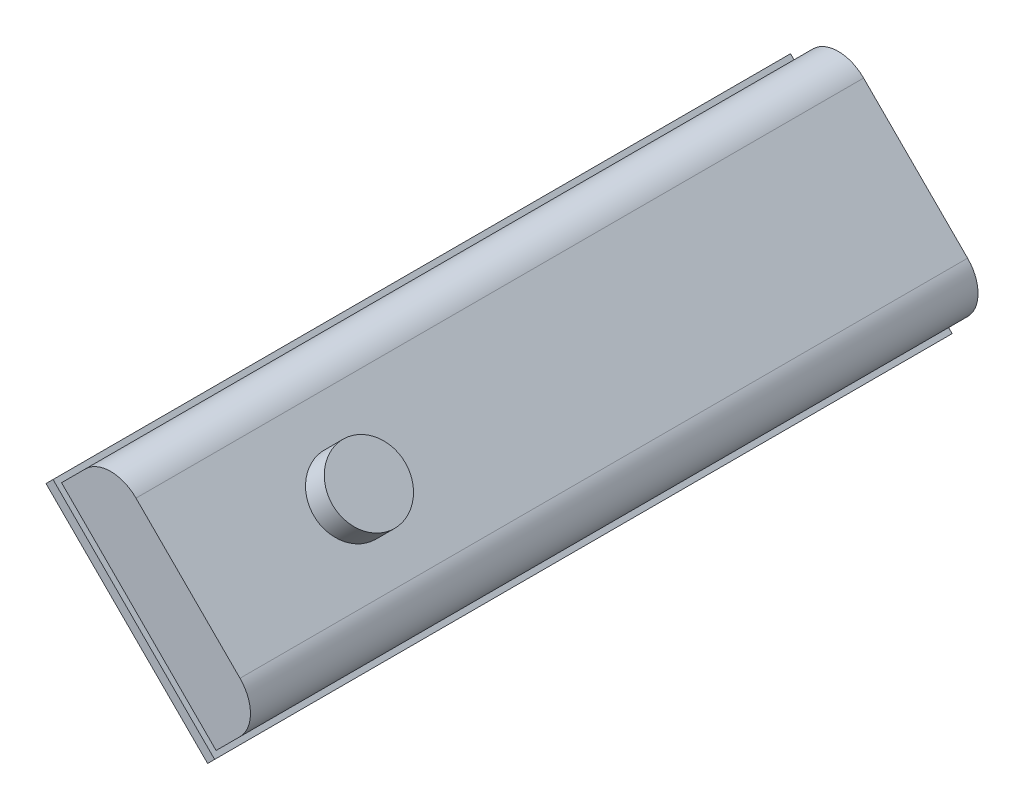
SolidWorks part; units mm, degrees
ref_plane "Front Plane" through (0, 0, 0) normal (0, 0, 1) x (1, 0, 0)
ref_plane "Top Plane" through (0, 0, 0) normal (0, 1, 0) x (1, 0, 0)
ref_plane "Right Plane" through (0, 0, 0) normal (1, 0, 0) x (0, 0, -1)
other "Configuration Table"
sketch "Sketch1" plane through (0, 0, 0) normal (0, 0, 1) x (1, 0, 0)
  line L0 (193.7119, 287.05) -> (287.05, 193.7119)
  line L1 (287.05, 193.7119) -> (305.7176, 212.3795)
  line L2 (305.7176, 242.9265) -> (242.9265, 305.7176)
  line L3 (212.3795, 305.7176) -> (193.7119, 287.05)
  arc A0 (305.7176, 212.3795) -> (305.7176, 242.9265) centre (290.4441, 227.653) ccw
  arc A1 (242.9265, 305.7176) -> (212.3795, 305.7176) centre (227.653, 290.4441) ccw
extrude "Cover" add sketch "Sketch1" along normal blind 439.28 from offset 375.38
sketch "Sketch2" plane through (0, 0, 0) normal (0, 0, 1) x (1, 0, 0)
  line L0 (191.5906, 289.1713) -> (289.1713, 191.5906)
  line L1 (289.1713, 191.5906) -> (293.414, 195.8332)
  line L2 (293.414, 195.8332) -> (195.8332, 293.414)
  line L3 (195.8332, 293.414) -> (191.5906, 289.1713)
extrude "Rail Flange" add sketch "Sketch2" along normal blind 445.28 from offset 378.38
sketch "Sketch3" plane through (274.3221, 274.3221, 0) normal (0.7071, 0.7071, 0) x (0, 0, -1)
  circle A0 centre (34, 0) radius 22
extrude "Oil Filler Cap" add sketch "Sketch3" along normal blind 16
